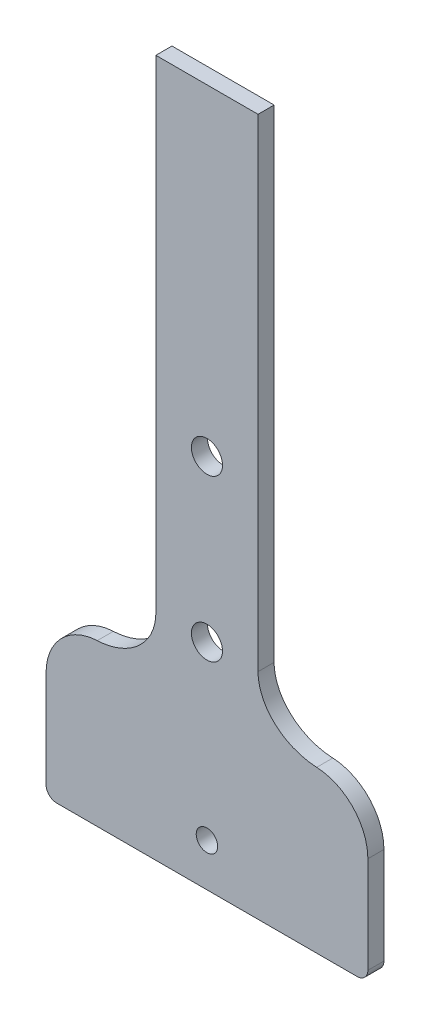
SolidWorks part; units mm, degrees
ref_plane "Front Plane" through (0, 0, 0) normal (0, 0, 1) x (1, 0, 0)
ref_plane "Top Plane" through (0, 0, 0) normal (0, 1, 0) x (1, 0, 0)
ref_plane "Right Plane" through (0, 0, 0) normal (1, 0, 0) x (0, 0, -1)
sketch "Sketch1" plane through (0, 0, 0) normal (0, 0, 1) x (1, 0, 0)
  line L12 (1, 0) -> (29, 0)
  line L13 (30, 1) -> (30, 10.0108)
  line L14 (19.7631, 20) -> (19.7631, 65)
  line L15 (19.7631, 65) -> (10.2369, 65)
  line L16 (10.2369, 65) -> (10.2369, 20)
  line L17 (0, 10.0108) -> (0, 1)
  circle A1 centre (15, 4) radius 1
  arc A4 (29, 0) -> (30, 1) centre (29, 1) ccw
  arc A5 (0, 1) -> (1, 0) centre (1, 1) ccw
  circle A6 centre (15, 20) radius 1.45
  circle A7 centre (15, 35) radius 1.45
  ellipse E4 centre (25.5366, 20) end of major axis (19.7631, 20) minor radius 5 (19.7631, 20) -> (25.23, 15.0071) ccw
  ellipse E5 centre (4.4634, 20) end of major axis (10.2369, 20) minor radius 5 (4.77, 15.0071) -> (10.2369, 20) ccw
  spline S4 degree 3 poles (30, 10.0108) (30, 10.3313) (29.9695, 10.6466) (29.8499, 11.2673) (29.7597, 11.5755) (29.5228, 12.1667) (29.3779, 12.4476) (29.0357, 12.9804) (28.8361, 13.2343) (28.3984, 13.6931) (28.1597, 13.9001) (27.642, 14.2689) (27.3629, 14.4299) (26.7876, 14.6924) (26.4887, 14.7962) (25.8674, 14.9469) (25.5502, 14.9923) (25.23, 15.0071) knots 0 0 0 0 0.125 0.125 0.25 0.25 0.375 0.375 0.5 0.5 0.625 0.625 0.75 0.75 0.875 0.875 1 1 1 1
  spline S5 degree 3 poles (4.77, 15.0071) (4.4498, 14.9923) (4.1363, 14.9473) (3.5218, 14.7992) (3.2181, 14.6948) (2.6385, 14.4308) (2.3646, 14.273) (1.8482, 13.9064) (1.6039, 13.6952) (1.166, 13.2368) (0.9703, 12.9886) (0.6258, 12.4544) (0.478, 12.1681) (0.2424, 11.5813) (0.1526, 11.2779) (0.0308, 10.6503) (0, 10.3313) (0, 10.0108) knots 0 0 0 0 0.125 0.125 0.25 0.25 0.375 0.375 0.5 0.5 0.625 0.625 0.75 0.75 0.875 0.875 1 1 1 1
extrude "Boss-Extrude1" add sketch "Sketch1" along normal blind 1.5
